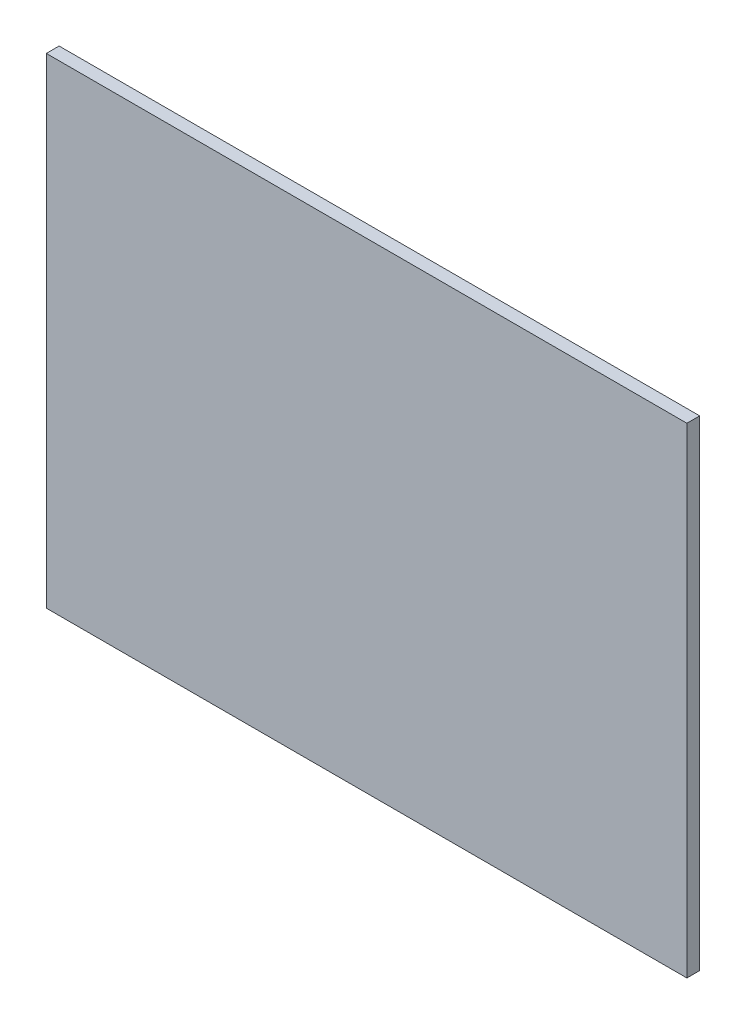
SolidWorks part; units mm, degrees
ref_plane "Front Plane" through (0, 0, 0) normal (0, 0, 1) x (1, 0, 0)
ref_plane "Top Plane" through (0, 0, 0) normal (0, 1, 0) x (1, 0, 0)
ref_plane "Right Plane" through (0, 0, 0) normal (1, 0, 0) x (0, 0, -1)
sketch "Sketch1" plane through (0, 0, 0) normal (0, 0, 1) x (1, 0, 0)
  line L1 (-250, -187.5) -> (250, -187.5)
  line L2 (-250, -187.5) -> (-250, 187.5)
  line L3 (-250, 187.5) -> (250, 187.5)
  line L4 (250, -187.5) -> (250, 187.5)
  line L5 (0, 187.5) -> (0, -187.5) construction
  line L6 (-250, 0) -> (250, 0) construction
  point P0 (0, 0)
  dimension "D1" = 500
  dimension "D2" = 375
extrude "Boss-Extrude1" add sketch "Sketch1" along normal blind 10
